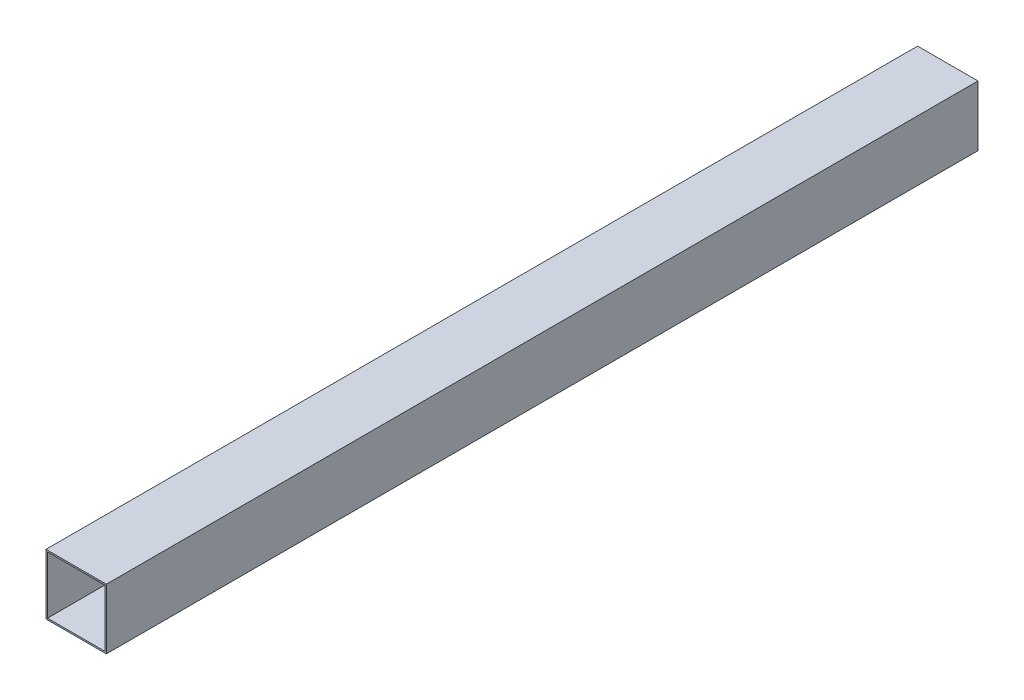
SolidWorks part; units mm, degrees
ref_plane "Alzado" through (0, 0, 0) normal (0, 0, 1) x (1, 0, 0)
ref_plane "Planta" through (0, 0, 0) normal (0, 1, 0) x (1, 0, 0)
ref_plane "Vista lateral" through (0, 0, 0) normal (1, 0, 0) x (0, 0, -1)
sketch "Croquis1" plane through (0, 0, 0) normal (0, 0, 1) x (1, 0, 0)
  line L0 (38.1, 0) -> (38.1, -76.2) construction
  line L1 (0, 0) -> (76.2, 0)
  line L2 (0, 0) -> (0, -76.2)
  line L3 (0, -76.2) -> (76.2, -76.2)
  line L4 (76.2, 0) -> (76.2, -76.2)
  line L6 (1.9, -74.3) -> (74.3, -74.3)
  line L7 (1.9, -74.3) -> (1.9, -1.9)
  line L8 (1.9, -1.9) -> (74.3, -1.9)
  line L9 (74.3, -74.3) -> (74.3, -1.9)
  line L10 (1.9, -74.3) -> (74.3, -1.9) construction
  line L11 (1.9, -1.9) -> (74.3, -74.3) construction
  point P7 (38.1, -38.1)
  dimension "D1" = 76.2
  dimension "D2" = 76.2
  dimension "D3" = 1.9
  dimension "D4" = 1.9
extrude "Saliente-Extruir1" add sketch "Croquis1" along normal blind 1100
